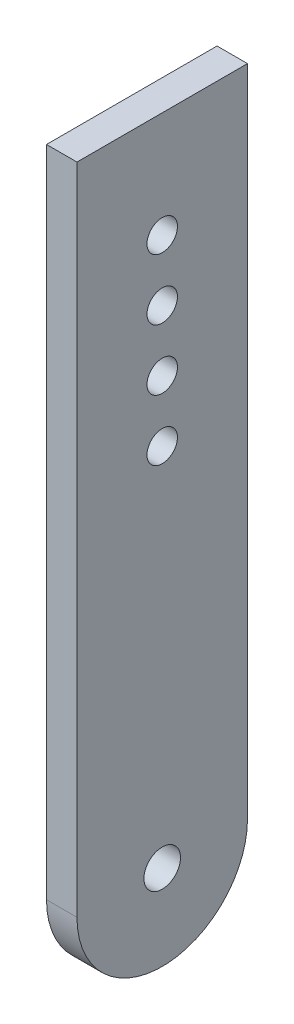
SolidWorks part; units mm, degrees
material "Acrylic (Medium-high impact)"
ref_plane "Ground" through (0, 0, 0) normal (0, 0, 1) x (1, 0, 0)
ref_plane "Right" through (0, 0, 0) normal (0, 1, 0) x (1, 0, 0)
ref_plane "Front" through (0, 0, 0) normal (1, 0, 0) x (0, 0, -1)
sketch "Sketch1" plane through (0, 0, 0) normal (1, 0, 0) x (0, 0, -1)
  line L0 (0, 0) -> (0, 46.6953) construction
  line L1 (-7, 0) -> (-7, 53.6953)
  line L2 (7, 0) -> (7, 53.6953)
  line L3 (-7, 53.6953) -> (7, 53.6953)
  arc A0 (-7, 0) -> (7, 0) centre (0, 0) ccw
  circle A2 centre (0, 0) radius 1.5
  circle A4 centre (0, 45) radius 1.25
  circle A8 centre (0, 40) radius 1.25
  circle A9 centre (0, 35) radius 1.25
  circle A10 centre (0, 30) radius 1.25
  point P3 (0, 30)
  dimension "D2" = 3
  dimension "D3" = 7
  dimension "D5" = 2.5
  dimension "D7" = 30
  dimension "D1" = 50
  dimension "D6" = 4
extrude "Boss-Extrude1" add sketch "Sketch1" along normal blind 2.5
